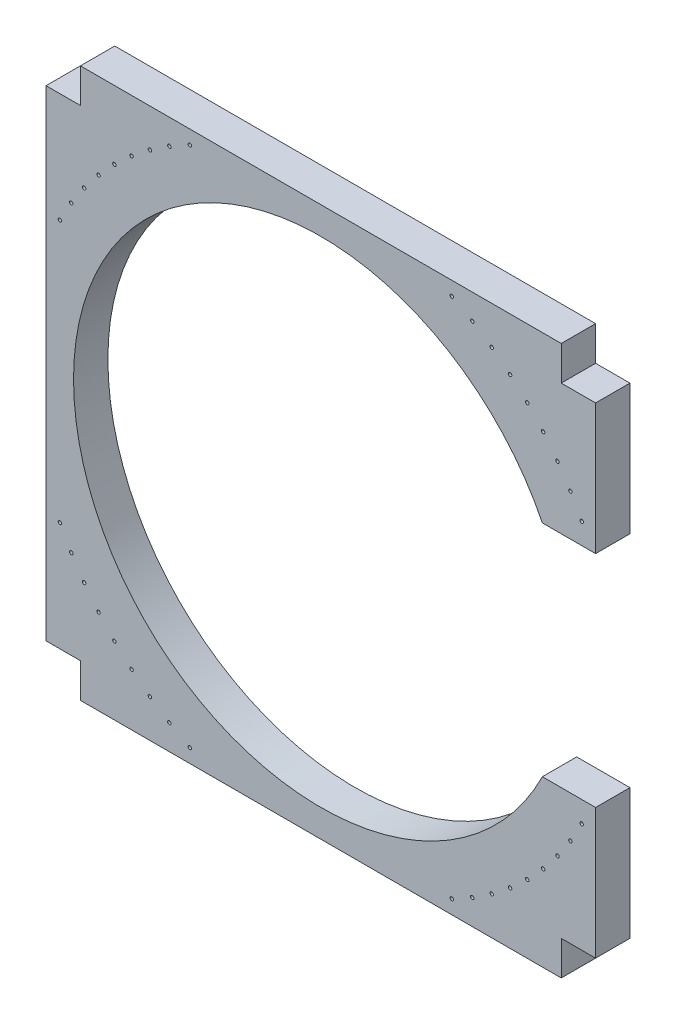
SolidWorks part; units mm, degrees
material "Balsa"
ref_plane "Plan de face" through (0, 0, 0) normal (0, 0, 1) x (1, 0, 0)
ref_plane "Plan de dessus" through (0, 0, 0) normal (0, 1, 0) x (1, 0, 0)
ref_plane "Plan de droite" through (0, 0, 0) normal (1, 0, 0) x (0, 0, -1)
sketch "Esquisse1" plane through (0, 0, 0) normal (0, 0, 1) x (1, 0, 0)
  line L0 (0, 40) -> (80, 40) construction
  line L1 (0, 80) -> (80, 80)
  line L2 (0, 80) -> (0, 0)
  line L3 (0, 0) -> (80, 0)
  line L4 (72.249, 24) -> (80, 24)
  line L5 (40, 80) -> (40, 0) construction
  line L6 (0, 80) -> (40, 40) construction
  line L7 (80, 24) -> (80, 0)
  line L8 (72.249, 56) -> (80, 56)
  line L9 (80, 56) -> (80, 80)
  arc A0 (72.249, 24) -> (72.249, 56) centre (40, 40) cw
  circle A1 centre (40, 40) radius 40 construction
  circle A2 centre (40, 40) radius 42.5 construction
  circle A3 centre (2.0185, 59.0698) radius 0.25
  circle A4 centre (7.6419, 67.5536) radius 0.25
  circle A5 centre (9.948, 70.052) radius 0.25
  circle A6 centre (3.6645, 62.0449) radius 0.25
  circle A7 centre (5.5429, 64.8789) radius 0.25
  circle A8 centre (20.9302, 77.9815) radius 0.25
  circle A9 centre (17.9551, 76.3355) radius 0.25
  circle A10 centre (15.1211, 74.4571) radius 0.25
  circle A11 centre (12.4464, 72.3581) radius 0.25
  circle A12 centre (67.5536, 72.3581) radius 0.25
  circle A13 centre (64.8789, 74.4571) radius 0.25
  circle A14 centre (62.0449, 76.3355) radius 0.25
  circle A15 centre (59.0698, 77.9815) radius 0.25
  circle A16 centre (74.4571, 64.8789) radius 0.25
  circle A17 centre (76.3355, 62.0449) radius 0.25
  circle A18 centre (70.052, 70.052) radius 0.25
  circle A19 centre (72.3581, 67.5536) radius 0.25
  circle A20 centre (77.9815, 59.0698) radius 0.25
  circle A21 centre (77.9815, 20.9302) radius 0.25
  circle A22 centre (72.3581, 12.4464) radius 0.25
  circle A23 centre (70.052, 9.948) radius 0.25
  circle A24 centre (76.3355, 17.9551) radius 0.25
  circle A25 centre (74.4571, 15.1211) radius 0.25
  circle A26 centre (59.0698, 2.0185) radius 0.25
  circle A27 centre (62.0449, 3.6645) radius 0.25
  circle A28 centre (64.8789, 5.5429) radius 0.25
  circle A29 centre (67.5536, 7.6419) radius 0.25
  circle A30 centre (12.4464, 7.6419) radius 0.25
  circle A31 centre (15.1211, 5.5429) radius 0.25
  circle A32 centre (17.9551, 3.6645) radius 0.25
  circle A33 centre (20.9302, 2.0185) radius 0.25
  circle A34 centre (5.5429, 15.1211) radius 0.25
  circle A35 centre (3.6645, 17.9551) radius 0.25
  circle A36 centre (9.948, 9.948) radius 0.25
  circle A37 centre (7.6419, 12.4464) radius 0.25
  circle A38 centre (2.0185, 20.9302) radius 0.25
  point P22 (40, 40)
  point P87 (80, 56)
  point P90 (72.249, 56)
  dimension "D3" = 36
  dimension "D4" = 85
  dimension "D7" = 0.5
  dimension "D9" = 3.4
  dimension "D1" = 80
  dimension "D2" = 80
  dimension "D10" = 3.4
  dimension "D11" = 3.4
  dimension "D12" = 3.4
  dimension "D14" = 32
extrude "Boss.-Extru.1" add sketch "Esquisse1" along normal blind 5
sketch "Esquisse2" plane through (0, 0, 0) normal (0, 0, -1) x (-1, 0, 0)
  line L0 (0, 0) -> (-80, 0) construction
  line L1 (0, 0) -> (-5, 0)
  line L2 (0, 0) -> (0, 5)
  line L3 (0, 5) -> (-5, 5)
  line L4 (-5, 0) -> (-5, 5)
  line L5 (-40, 0) -> (-40, 80) construction
  line L6 (-80, 80) -> (0, 80) construction
  line L7 (0, 40) -> (-80, 40) construction
  line L8 (-75, 0) -> (-75, 5)
  line L9 (0, 80) -> (0, 0) construction
  line L10 (-80, 5) -> (-75, 5)
  line L11 (-80, 0) -> (-80, 5)
  line L12 (-80, 0) -> (-75, 0)
  line L13 (-80, 80) -> (-75, 80)
  line L14 (-80, 80) -> (-80, 75)
  line L15 (-80, 75) -> (-75, 75)
  line L16 (-75, 80) -> (-75, 75)
  line L17 (-5, 80) -> (-5, 75)
  line L18 (0, 75) -> (-5, 75)
  line L19 (0, 80) -> (0, 75)
  line L20 (0, 80) -> (-5, 80)
  dimension "D1" = 5
  dimension "D2" = 5
extrude "Créneaux -" cut sketch "Esquisse2" against normal blind 5
